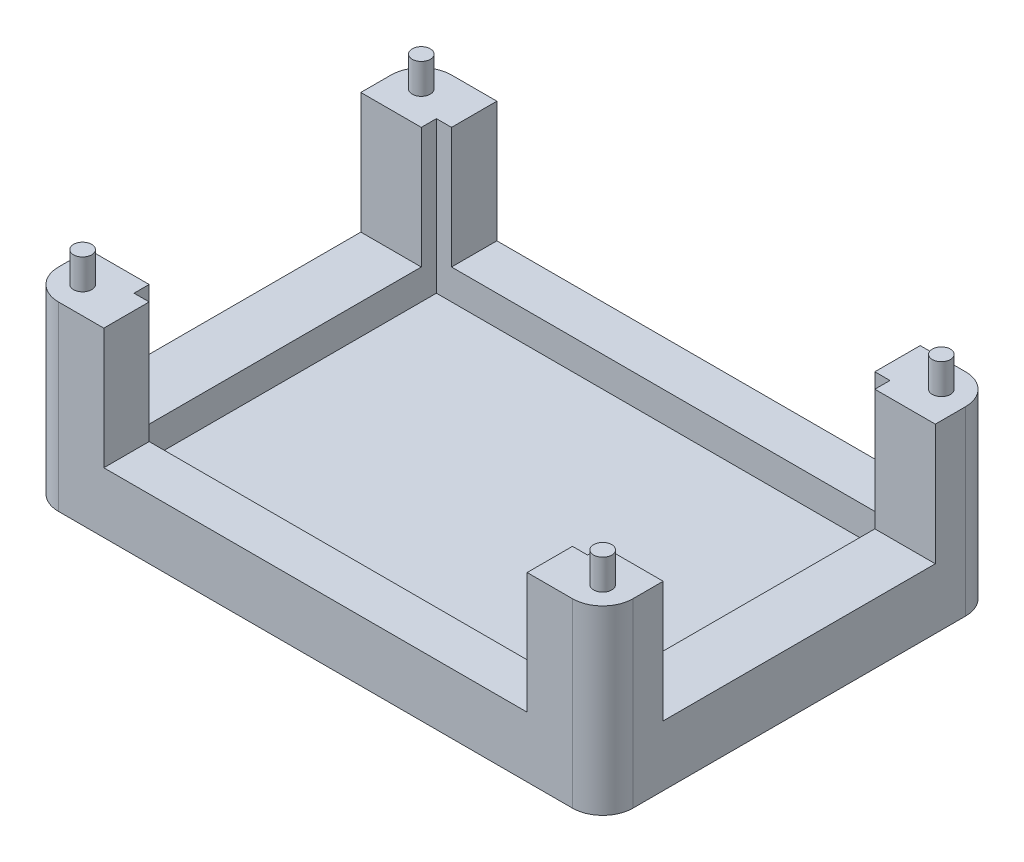
SolidWorks part; units mm, degrees
ref_plane "Front Plane" through (0, 0, 0) normal (0, 0, 1) x (1, 0, 0)
ref_plane "Top Plane" through (0, 0, 0) normal (0, 1, 0) x (1, 0, 0)
ref_plane "Right Plane" through (0, 0, 0) normal (1, 0, 0) x (0, 0, -1)
sketch "Sketch1" plane through (0, 0, 0) normal (0, 1, 0) x (1, 0, 0)
  line L1 (-47.5, 32.5) -> (47.5, 32.5)
  line L2 (-47.5, 32.5) -> (-47.5, -32.5)
  line L3 (-47.5, -32.5) -> (47.5, -32.5)
  line L4 (47.5, 32.5) -> (47.5, -32.5)
  line L5 (-47.5, 32.5) -> (47.5, -32.5) construction
  line L6 (-47.5, -32.5) -> (47.5, 32.5) construction
  point P0 (0, 0)
  dimension "D1" = 65
  dimension "D2" = 95
extrude "Boss-Extrude1" add sketch "Sketch1" along normal blind 30
fillet "Fillet1" radius 5 4 edges at (-47.5, 15, -32.5) (-47.5, 15, 32.5) (47.5, 15, -32.5) (47.5, 15, 32.5)
sketch "Sketch2" plane through (0, 30, 0) normal (0, 1, 0) x (1, 0, 0)
  line L1 (-37.5, 25) -> (37.5, 25)
  line L2 (-37.5, 25) -> (-37.5, -25)
  line L3 (-37.5, -25) -> (37.5, -25)
  line L4 (37.5, 25) -> (37.5, -25)
  line L5 (-37.5, 25) -> (37.5, -25) construction
  line L6 (-37.5, -25) -> (37.5, 25) construction
  point P0 (0, 0)
  dimension "D1" = 50
  dimension "D2" = 75
extrude "Cut-Extrude1" cut sketch "Sketch2" against normal offset from surface (25 mm away) 5 up to face at (0, 0, 0)
sketch "Sketch3" plane through (0, 30, 0) normal (0, 1, 0) x (1, 0, 0)
  line L0 (0, -15.7681) -> (0, 47.9361) construction
  line L1 (-63.9857, 0) -> (62.4074, 0) construction
  circle A0 centre (43, 28) radius 1.5
  circle A1 centre (-43, 28) radius 1.5
  circle A2 centre (43, -28) radius 1.5
  circle A3 centre (-43, -28) radius 1.5
  point P13 (0, 0)
  point P14 (0, 0)
  point P15 (0, 0)
  point P16 (0, 0)
  point P17 (0, 0)
  point P18 (43, -28)
  dimension "D1" = 3
  dimension "D2" = 56
  dimension "D3" = 86
extrude "Boss-Extrude2" add sketch "Sketch3" along normal blind 5
sketch "Sketch4" plane through (47.5, 0, 0) normal (1, 0, 0) x (0, 0, -1)
  line L0 (-27.5, 30) -> (27.5, 30) construction
  line L2 (22.5, 50) -> (-22.5, 50)
  line L3 (22.5, 50) -> (22.5, 10)
  line L4 (22.5, 10) -> (-22.5, 10)
  line L5 (-22.5, 50) -> (-22.5, 10)
  line L6 (22.5, 50) -> (-22.5, 10) construction
  line L7 (22.5, 10) -> (-22.5, 50) construction
  point P3 (0, 30)
  dimension "D1" = 45
  dimension "D2" = 20
extrude "Cut-Extrude2" cut sketch "Sketch4" against normal through all
sketch "Sketch5" plane through (0, 0, 32.5) normal (0, 0, 1) x (1, 0, 0)
  line L0 (-42.5, 30) -> (42.5, 30) construction
  line L1 (-35, 50) -> (35, 50)
  line L2 (-35, 50) -> (-35, 10)
  line L3 (-35, 10) -> (35, 10)
  line L4 (35, 50) -> (35, 10)
  line L5 (-35, 50) -> (35, 10) construction
  line L6 (-35, 10) -> (35, 50) construction
  point P0 (0, 30)
  dimension "D1" = 20
  dimension "D2" = 70
extrude "Cut-Extrude3" cut sketch "Sketch5" against normal through all
